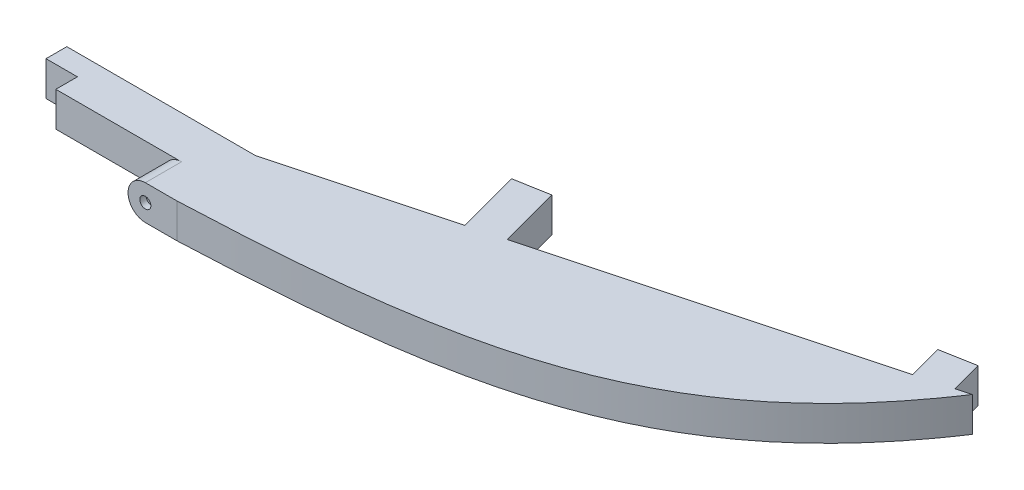
SolidWorks part; units mm, degrees
ref_plane "Alzado" through (0, 0, 0) normal (0, 0, 1) x (1, 0, 0)
ref_plane "Planta" through (0, 0, 0) normal (0, 1, 0) x (1, 0, 0)
ref_plane "Vista lateral" through (0, 0, 0) normal (1, 0, 0) x (0, 0, -1)
sketch "Croquis2" plane through (0, 0, 0) normal (0, 1, 0) x (1, 0, 0)
  line L0 (0, 0) -> (90, 0) construction
  line L1 (0, 0) -> (0, 12.5)
  line L2 (90, 0) -> (90, 39) construction
  line L3 (0, 12.5) -> (90, 36.6154)
  spline S0 degree 4 poles (-9.0154, -0.3049) (-8.717, -0.2963) (-8.098, -0.278) (-7.171, -0.253) (-5.1209, -0.1858) (-3.7226, -0.1427) (-0.7631, -0.031) (0.4662, 0.018) (2.9737, 0.1251) (4.5401, 0.2003) (6.5666, 0.3007) (8.3253, 0.3977) (10.2393, 0.5087) (12.0657, 0.6246) (14.4015, 0.7831) (17.1746, 0.9915) (20.4243, 1.2671) (24.124, 1.6319) (28.7465, 2.1606) (34.1867, 2.9164) (39.5992, 3.8695) (44.9594, 5.0771) (49.3618, 6.2804) (52.9107, 7.4009) (56.4082, 8.6739) (59.8414, 10.1115) (63.1969, 11.723) (66.46, 13.5145) (69.6167, 15.4877) (72.6542, 17.6398) (75.5626, 19.9636) (78.4114, 22.5164) (80.6372, 24.7501) (82.3142, 26.5769) (83.5002, 27.9419) (84.1665, 28.7295) (84.8247, 29.5295) (85.4679, 30.3306) (86.1096, 31.1529) (86.7258, 31.9596) (87.3592, 32.8149) (87.9353, 33.6053) (88.5854, 34.5294) (89.0773, 35.2347) (89.8261, 36.3501) (90.1738, 36.8773) (90.9035, 38.0031) (91.3552, 38.7262) (91.9126, 39.6241) (92.3432, 40.3399) (92.8683, 41.2207) (93.3254, 42.0073) (93.791, 42.8213) (94.2413, 43.6262) (94.6008, 44.2772) (94.8664, 44.7654) (95.0423, 45.0919) (95.13, 45.2553) knots 0 0 0 0 0 0.009318 0.018636 0.037271 0.055907 0.074543 0.089942 0.105341 0.12074 0.13614 0.151539 0.166938 0.182337 0.197736 0.228535 0.259333 0.290131 0.32093 0.382526 0.441205 0.472004 0.502802 0.5336 0.564399 0.595197 0.625995 0.656794 0.687592 0.71839 0.749189 0.779987 0.814189 0.82274 0.83129 0.839841 0.848391 0.856942 0.865492 0.874043 0.882593 0.891144 0.899694 0.908245 0.916795 0.925316 0.933837 0.942358 0.950879 0.957019 0.963159 0.975439 0.98158 0.98772 0.99386 1 1 1 1 1 construction
  spline S1 degree 4 poles (0, 0) (0.3914, 0.0158) (1.187, 0.0488) (2.9737, 0.1251) (4.5401, 0.2003) (6.5666, 0.3007) (8.3253, 0.3977) (10.2393, 0.5087) (12.0657, 0.6246) (14.4015, 0.7831) (17.1746, 0.9915) (20.4243, 1.2671) (24.124, 1.6319) (28.7465, 2.1606) (34.1867, 2.9164) (39.5992, 3.8695) (44.9594, 5.0771) (49.3618, 6.2804) (52.9107, 7.4009) (56.4082, 8.6739) (59.8414, 10.1115) (63.1969, 11.723) (66.46, 13.5145) (69.6167, 15.4877) (72.6542, 17.6398) (75.5626, 19.9636) (78.4114, 22.5164) (80.6372, 24.7501) (82.3142, 26.5769) (83.5002, 27.9419) (84.1665, 28.7295) (84.8247, 29.5295) (85.4679, 30.3306) (86.1096, 31.1529) (86.7258, 31.9596) (87.3592, 32.8149) (87.9353, 33.6053) (88.5854, 34.5294) (89.0773, 35.2347) (89.6394, 36.072) (89.8802, 36.4339) (90, 36.6154) knots 0.074543 0.074543 0.074543 0.074543 0.074543 0.089942 0.105341 0.12074 0.13614 0.151539 0.166938 0.182337 0.197736 0.228535 0.259333 0.290131 0.32093 0.382526 0.441205 0.472004 0.502802 0.5336 0.564399 0.595197 0.625995 0.656794 0.687592 0.71839 0.749189 0.779987 0.814189 0.82274 0.83129 0.839841 0.848391 0.856942 0.865492 0.874043 0.882593 0.891144 0.899694 0.908245 0.916795 0.916795 0.916795 0.916795 0.916795
  dimension "D1" = 36.6154
  dimension "D2" = 12.5
  dimension "D3" = 90
extrude "Saliente-Extruir1" add sketch "Croquis2" along normal blind 5.5
sketch "Croquis3" plane through (0, 0, 0) normal (-1, 0, 0) x (0, 0, 1)
  line L0 (0, 5.5) -> (0, 0) construction
  line L1 (-12.5, 0) -> (0, 0)
  line L2 (-12.5, 0) -> (-12.5, 5.5)
  line L3 (-12.5, 5.5) -> (0, 5.5)
  line L4 (0, 0) -> (0, 5.5)
  line L5 (-12.5, 0) -> (0, 5.5) construction
  line L6 (-12.5, 5.5) -> (0, 0) construction
  line L7 (-12.5, 2.75) -> (0, 2.75) construction
  line L8 (-12.5, 5.5) -> (-12.5, 0) construction
  point P0 (-6.25, 2.75)
  dimension "D1" = 12.5
  dimension "D2" = 5.5
extrude "Saliente-Extruir2" add sketch "Croquis3" along normal blind 25
sketch "Croquis6" plane through (0, 0, 0) normal (0, 0, 1) x (1, 0, 0)
  line L0 (-5, 2.75) -> (-25, 2.75) construction
  line L2 (-25, 0) -> (-25, 5.5) construction
  circle A0 centre (-5, 2.75) radius 0.88
  dimension "D1" = 20
  dimension "D2" = 1.76
extrude "Cortar-Extruir3" cut sketch "Croquis6" against normal blind 1
sketch "Croquis5" plane through (0, 0, 0) normal (0, 0, 1) x (1, 0, 0)
  line L4 (-25, 5.5) -> (0, 5.5) construction
  line L5 (-25, 0) -> (-25, 5.5)
  line L6 (-25, 0) -> (0, 0) construction
  line L7 (-34.55, 0) -> (-25, 0)
  line L8 (-25, 5.5) -> (-5, 5.5)
  circle A0 centre (-5, 2.75) radius 2.75
  line M8 (0, 5.5) -> (-25, 5.5)
  line M9 (-25, 5.5) -> (-25, 0)
  line M10 (-25, 0) -> (0, 0)
  dimension "D2" = 5.5
extrude "Cortar-Extruir4" cut sketch "Croquis5" against normal blind 5.75 contours A0 M8 M9 M10
sketch "Croquis7" plane through (-25, 0, 0) normal (-1, 0, 0) x (0, 0, 1)
  line L0 (-9.1875, 5.5) -> (-9.1875, -0.5)
  line L1 (-12.625, -0.5) -> (-5.75, -0.5)
  line L2 (-12.625, -0.5) -> (-12.625, 5.5)
  line L3 (-12.625, 5.5) -> (-5.75, 5.5)
  line L4 (-5.75, -0.5) -> (-5.75, 5.5)
  line L5 (-12.625, -0.5) -> (-5.75, 5.5) construction
  line L6 (-12.625, 5.5) -> (-5.75, -0.5) construction
  point P0 (-9.1875, 2.5)
  point P8 (-9.1875, 2.5)
  line M2 (-5.75, 5.5) -> (-12.5, 5.5)
  line M3 (-12.5, 5.5) -> (-12.5, 0)
  line M4 (-12.5, 0) -> (-5.75, 0)
extrude "Saliente-Extruir3" add sketch "Croquis7" along normal blind 5 contours L0 M2 M3 M4
sketch "Croquis10" plane through (0, 5.5, 0) normal (0, 1, 0) x (1, 0, 0)
  line L0 (0, 12.5) -> (0, 15)
  line L1 (0, 15) -> (-30, 15)
  line L2 (-30, 15) -> (-30, 20)
  line L3 (0, 12.5) -> (90, 36.6154)
  line L4 (90, 36.6154) -> (88.7059, 41.4451)
  line L5 (88.7059, 41.4451) -> (-30, 20)
  line L6 (28.9778, 20.2646) -> (26.3223, 30.175) construction
  line L7 (26.3215, 19.5528) -> (23.6067, 29.6844)
  line L8 (31.6341, 20.9763) -> (29.0378, 30.6656)
  line L9 (85.1704, 35.3213) -> (83.7685, 40.5531) construction
  line L10 (87.8267, 36.0331) -> (86.4841, 41.0437)
  line L11 (82.5141, 34.6096) -> (81.053, 40.0625)
  dimension "D1" = 2.5
  dimension "D2" = 30
  dimension "D3" = 5
  dimension "D4" = 5
  dimension "D5" = 30
  dimension "D6" = 2.75
  dimension "D7" = 2.75
  dimension "D8" = 5
  dimension "D9" = 2.75
  dimension "D10" = 2.75
extrude "Saliente-Extruir6" add sketch "Croquis10" against normal blind 5.5 contours L3 L8 L5 L7 | L11 L3 L10 L5
equation "\"A_ALETA\"= ( ( ( tan ( \"ANG_ALETA\" ) ) * \"L_ALETA\" ) + \"A_BASE\" )"
equation "\"A_CAJA\"= ( 2 * \"A_BASE\" ) + \"GAP_ALETAS\""
equation "\"D1@Croquis2\" = \"A_BASE\""
equation "\"L_ALETA\"=90.000000"
equation "\"D3@Croquis2\" = \"L_ALETA\""
equation "\"TAU_ALETA\"= ( \"L_ALETA\" / ( log ( ( \"A_ALETA\" ) + 1 ) ) )"
equation "\"E_ALETA\"=5.5"
equation "\"R_SONDA\"= 2.05"
equation "\"D_SONDA\"=20.000000"
equation "\"L_CAJA\"=25.000000"
equation "\"D2@Croquis2\"=\"A_BASE\""
equation "\"D1@Saliente-Extruir1\"=\"E_ALETA\""
equation "\"D1@Croquis3\"=\"A_BASE\""
equation "\"D1@Saliente-Extruir2\"=\"L_CAJA\""
equation "\"A_BASE\"= ( \"L_DIE\" - \"E_CAJA\" )"
equation "\"E_CAJA\"= 2.5"
equation "\"W_CAJA\"= \"A_CAJA\" * \"CONST_CAJA\""
equation "\"W_CONC\"= ( \"W_CAJA\" / \"CONST_CONC\" ) "
equation "\"A_CONC\"= ( \"A_CAJA\" / \"CONST_CONC\" )"
equation "\"L_CONC\"= \"D_SONDA\" - \"OFFSET_CONC\""
equation "\"W_ALETA\"=70.000000"
equation "\"GAP_ALETAS\"=2"
equation "\"L_DIE_SONDA\"= ( \"GAP_ALETAS\" / 4 )"
equation "\"D1@Croquis5\" = \"L_CONC\""
equation "\"D1@Cortar-Extruir2\" = \"A_BASE\" - ( ( \"A_CAJA\" - \"A_CONC\" ) / 2 )"
equation "\"CONST_CONC\"=2.000000"
equation "\"K\"= 1.5"
equation "\"L_DIE\"= 15"
equation "\"L_CI\"= 18"
equation "\"D1@Croquis6\" = \"D_SONDA\""
equation "\"D2@Croquis6\"=\"R_C_SONDA\" * 2 +\"TOLERANCIA\""
equation "\"D1@Cortar-Extruir3\" = \"L_CI\" - \"E_CAJA\" - \"A_BASE\" - \"GAP_ALETAS\""
equation "\"CONST_CAJA\"=2.000000"
equation "\"ANG_ALETA\"=15.000000"
equation "\"D1@Cortar-Extruir4\" = \"A_BASE\" - ( ( \"A_CAJA\" - \"A_CONC\" ) / 2 )"
equation "\"R_C_SONDA\"= 0.63"
equation "\"TOLERANCIA\"= 0.5"
equation "\"OFFSET_CONC\"= ( 2 * \"R_TORNILLO\" )"
equation "\"R_TORNILLO\"=2.600000"
equation "\"D2@Croquis3\" = \"E_ALETA\""
equation "\"D1@Saliente-Extruir3\"=\"E_CAJA\"*2"
equation "\"D1@Croquis10\"=\"E_CAJA\""
equation "\"D2@Croquis10\"=\"L_CAJA\"+\"E_CAJA\"*2"
equation "\"D3@Croquis10\"=\"E_CAJA\"*2"
equation "\"D4@Croquis10\"=\"E_CAJA\"*2"
equation "\"D6@Croquis10\"=\"E_ALETA\"/2"
equation "\"D7@Croquis10\"=\"E_ALETA\"/2"
equation "\"D9@Croquis10\" = \"E_ALETA\" / 2"
equation "\"D10@Croquis10\"=\"E_ALETA\"/2"
equation "\"D1@Saliente-Extruir6\"=\"E_ALETA\""
equation "\"ALARGUE\"=15"
